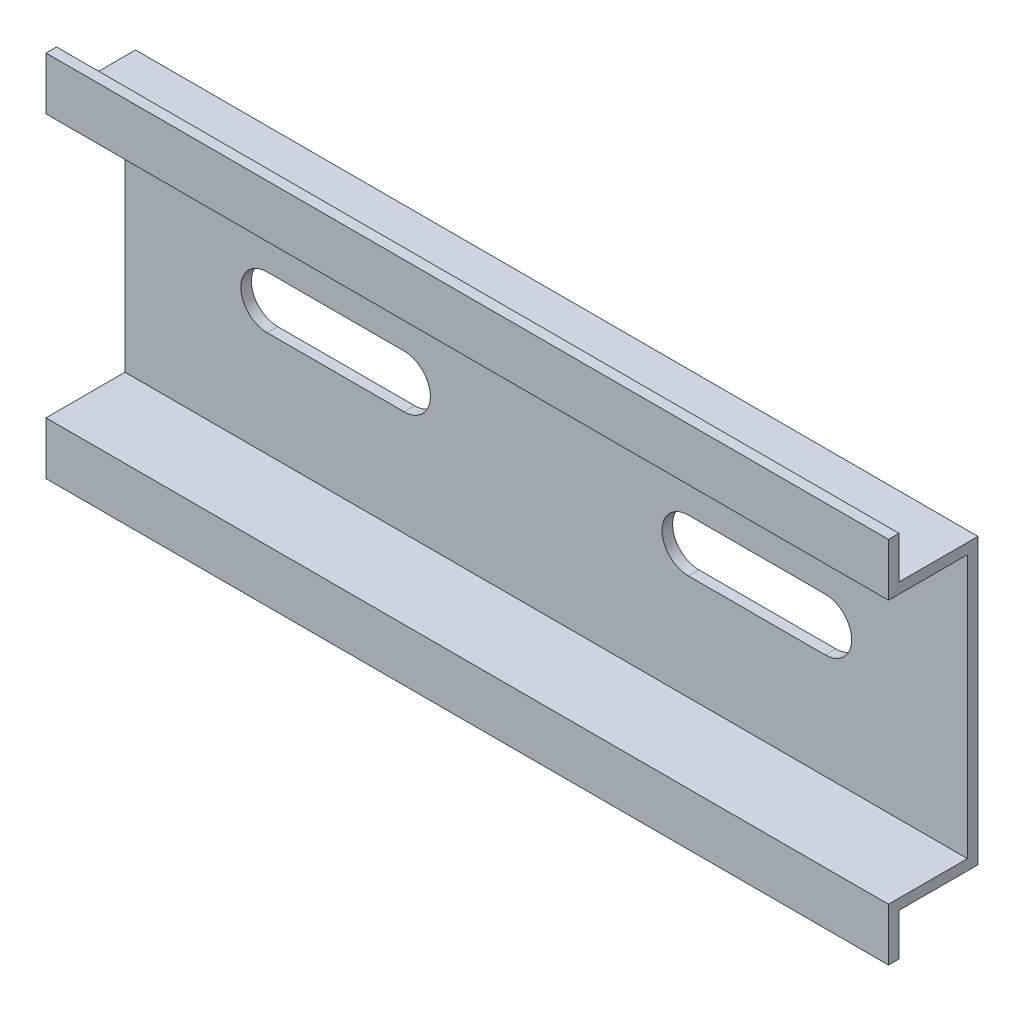
SolidWorks part; units mm, degrees
ref_plane "Piano frontale" through (0, 0, 0) normal (0, 0, 1) x (1, 0, 0)
ref_plane "Piano superiore" through (0, 0, 0) normal (0, 1, 0) x (1, 0, 0)
ref_plane "Piano destro" through (0, 0, 0) normal (1, 0, 0) x (0, 0, -1)
sketch "Schizzo1" plane through (0, 0, 0) normal (1, 0, 0) x (0, 0, -1)
  line L0 (0, 35) -> (0, 30)
  line L1 (0, 30) -> (7.5, 30)
  line L2 (7.5, 30) -> (7.5, 5)
  line L3 (7.5, 5) -> (0, 5)
  line L4 (0, 5) -> (0, 0)
  line L5 (1, 35) -> (1, 31)
  line L6 (1, 31) -> (8.5, 31)
  line L7 (8.5, 31) -> (8.5, 4)
  line L8 (8.5, 4) -> (1, 4)
  line L9 (1, 4) -> (1, 0)
  line L10 (0, 35) -> (1, 35)
  line L11 (0, 0) -> (1, 0)
  dimension "D1" = 35
  dimension "D2" = 25
  dimension "D3" = 7.5
  dimension "D4" = 5
  dimension "D5" = 1
extrude "Estrusione-Estrusione1" add sketch "Schizzo1" along normal blind 80
sketch "Schizzo2" plane through (0, 0, -7.5) normal (0, 0, 1) x (1, 0, 0)
  line L0 (13.5, 17.5) -> (26.5, 17.5) construction
  line L1 (13.5, 20) -> (26.5, 20)
  line L2 (13.5, 15) -> (26.5, 15)
  line L3 (80, 35) -> (0, 35) construction
  line L4 (0, 30) -> (0, 5) construction
  line L5 (53.5, 17.5) -> (66.5, 17.5) construction
  line L6 (53.5, 20) -> (66.5, 20)
  line L7 (53.5, 15) -> (66.5, 15)
  arc A0 (13.5, 20) -> (13.5, 15) centre (13.5, 17.5) ccw
  arc A1 (26.5, 15) -> (26.5, 20) centre (26.5, 17.5) ccw
  arc A2 (53.5, 20) -> (53.5, 15) centre (53.5, 17.5) ccw
  arc A3 (66.5, 15) -> (66.5, 20) centre (66.5, 17.5) ccw
  point P2 (20, 17.5)
  point P7 (11, 17.5)
  point P8 (29, 17.5)
  point P14 (0, 0)
  point P16 (60, 17.5)
  dimension "D1" = 18
  dimension "D2" = 5
  dimension "D3" = 17.5
  dimension "D4" = 20
  dimension "D5" = 2
extrude "Taglio-Estrusione1" cut sketch "Schizzo2" against normal up to next
